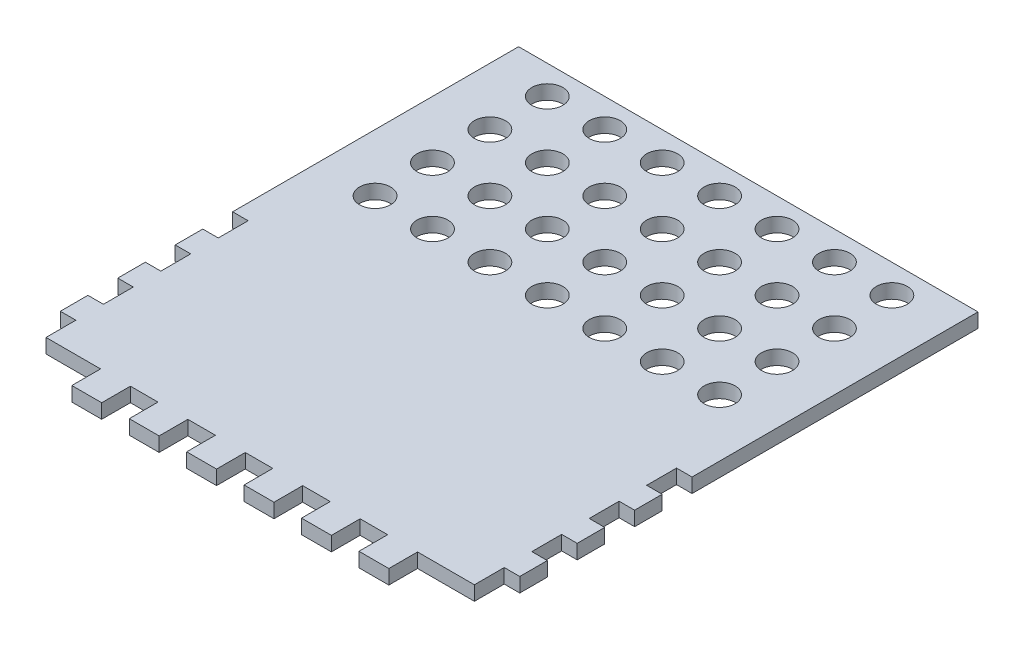
SolidWorks part; units mm, degrees
ref_plane "Front Plane" through (0, 0, 0) normal (0, 0, 1) x (1, 0, 0)
ref_plane "Top Plane" through (0, 0, 0) normal (0, 1, 0) x (1, 0, 0)
ref_plane "Right Plane" through (0, 0, 0) normal (1, 0, 0) x (0, 0, -1)
sketch "Sketch1" plane through (0, 0, 0) normal (0, 1, 0) x (1, 0, 0)
  line L1 (-50.8, -53.975) -> (50.8, -53.975)
  line L2 (-50.8, -53.975) -> (-50.8, 53.975)
  line L3 (-50.8, 53.975) -> (50.8, 53.975)
  line L4 (50.8, -53.975) -> (50.8, 53.975)
  line L5 (-50.8, -53.975) -> (50.8, 53.975) construction
  line L6 (-50.8, 53.975) -> (50.8, -53.975) construction
  line L11 (-41.275, -53.975) -> (41.275, 53.975) construction
  line L12 (-41.275, 53.975) -> (41.275, -53.975) construction
  point P0 (0, 0)
  point P5 (0, 0)
  dimension "D1" = 101.6
  dimension "D2" = 107.95
extrude "Boss-Extrude1" add sketch "Sketch1" along normal blind 3.175
sketch "Sketch2" plane through (0, 3.175, 0) normal (0, 1, 0) x (1, 0, 0)
  line L37 (22.098, -47.625) -> (28.194, -47.625)
  line L49 (28.194, -47.625) -> (28.194, -54.229)
  line L69 (0, 0) -> (0, -10.121) construction
  line L74 (-50.8, 53.975) -> (-50.8, -53.975) construction
  line L75 (-47.371, 28.448) -> (-50.8, 28.448)
  line L76 (-47.371, 28.448) -> (-47.371, 35.052)
  line L78 (-50.8, 28.448) -> (-50.8, 35.052)
  line L79 (-47.371, 22.479) -> (-50.8, 22.479)
  line L80 (-47.371, 22.479) -> (-47.371, 15.875)
  line L81 (-47.371, 15.875) -> (-50.8, 15.875)
  line L82 (-50.8, 22.479) -> (-50.8, 15.875)
  line L83 (-47.371, 9.779) -> (-50.8, 9.779)
  line L84 (-47.371, 9.779) -> (-47.371, 3.175)
  line L85 (-47.371, 3.175) -> (-50.8, 3.175)
  line L86 (-50.8, 9.779) -> (-50.8, 3.175)
  line L87 (-47.371, -2.921) -> (-50.8, -2.921)
  line L88 (-47.371, -2.921) -> (-47.371, -9.525)
  line L89 (-47.371, -9.525) -> (-50.8, -9.525)
  line L90 (-50.8, -2.921) -> (-50.8, -9.525)
  line L91 (-47.371, -15.621) -> (-50.8, -15.621)
  line L92 (-47.371, -15.621) -> (-47.371, -22.225)
  line L93 (-47.371, -22.225) -> (-50.8, -22.225)
  line L94 (-50.8, -15.621) -> (-50.8, -22.225)
  line L95 (-47.371, -28.321) -> (-50.8, -28.321)
  line L96 (-47.371, -28.321) -> (-47.371, -34.925)
  line L97 (-47.371, -34.925) -> (-50.8, -34.925)
  line L98 (-50.8, -28.321) -> (-50.8, -34.925)
  line L99 (-47.371, -41.021) -> (-50.8, -41.021)
  line L100 (-47.371, -41.021) -> (-47.371, -47.625)
  line L102 (-50.8, -41.021) -> (-50.8, -47.625)
  line L118 (50.8, -41.021) -> (50.8, -47.625)
  line L120 (47.371, -41.021) -> (47.371, -47.625)
  line L121 (47.371, -41.021) -> (50.8, -41.021)
  line L122 (50.8, -28.321) -> (50.8, -34.925)
  line L123 (47.371, -34.925) -> (50.8, -34.925)
  line L124 (47.371, -28.321) -> (47.371, -34.925)
  line L125 (47.371, -28.321) -> (50.8, -28.321)
  line L126 (50.8, -15.621) -> (50.8, -22.225)
  line L127 (47.371, -22.225) -> (50.8, -22.225)
  line L128 (47.371, -15.621) -> (47.371, -22.225)
  line L129 (47.371, -15.621) -> (50.8, -15.621)
  line L130 (50.8, -2.921) -> (50.8, -9.525)
  line L131 (47.371, -9.525) -> (50.8, -9.525)
  line L132 (47.371, -2.921) -> (47.371, -9.525)
  line L133 (47.371, -2.921) -> (50.8, -2.921)
  line L134 (50.8, 9.779) -> (50.8, 3.175)
  line L135 (47.371, 3.175) -> (50.8, 3.175)
  line L136 (47.371, 9.779) -> (47.371, 3.175)
  line L137 (47.371, 9.779) -> (50.8, 9.779)
  line L138 (50.8, 22.479) -> (50.8, 15.875)
  line L139 (47.371, 15.875) -> (50.8, 15.875)
  line L140 (47.371, 22.479) -> (47.371, 15.875)
  line L141 (47.371, 22.479) -> (50.8, 22.479)
  line L150 (-47.371, -53.721) -> (-50.8, -53.721) [skipped]
  line L151 (-47.371, -53.721) -> (-47.371, -60.325) [skipped]
  line L152 (-47.371, -60.325) -> (-50.8, -60.325) [skipped]
  line L153 (-50.8, -53.721) -> (-50.8, -60.325) [skipped]
  line L154 (-50.8, 35.052) -> (-47.371, 35.052)
  line L155 (50.8, 35.052) -> (47.371, 35.052)
  line L156 (50.8, 28.448) -> (50.8, 35.052)
  line L157 (47.371, 28.448) -> (47.371, 35.052)
  line L158 (47.371, 28.448) -> (50.8, 28.448)
  line L159 (-47.371, -47.625) -> (-35.306, -47.625)
  line L160 (-35.306, -47.625) -> (-35.306, -54.229)
  line L161 (-35.306, -54.229) -> (-28.702, -54.229)
  line L162 (-28.702, -54.229) -> (-28.702, -47.625)
  line L163 (-28.702, -47.625) -> (-22.606, -47.625)
  line L164 (-22.606, -47.625) -> (-22.606, -54.229)
  line L165 (-22.606, -54.229) -> (-16.002, -54.229)
  line L166 (-16.002, -54.229) -> (-16.002, -47.625)
  line L167 (-16.002, -47.625) -> (-9.906, -47.625)
  line L168 (-9.906, -47.625) -> (-9.906, -54.229)
  line L169 (-9.906, -54.229) -> (-3.302, -54.229)
  line L170 (-3.302, -54.229) -> (-3.302, -47.625)
  line L171 (-3.302, -47.625) -> (2.794, -47.625)
  line L172 (2.794, -47.625) -> (2.794, -54.229)
  line L173 (2.794, -54.229) -> (9.398, -54.229)
  line L174 (9.398, -54.229) -> (9.398, -47.625)
  line L175 (9.398, -47.625) -> (15.494, -47.625)
  line L176 (15.494, -47.625) -> (15.494, -54.229)
  line L177 (15.494, -54.229) -> (22.098, -54.229)
  line L178 (22.098, -54.229) -> (22.098, -47.625)
  line L180 (-50.8, -47.625) -> (-50.8, -92.545)
  line L181 (-47.371, -47.625) -> (-50.8, -47.625) [skipped]
  line L182 (-50.8, -92.545) -> (50.8, -92.545)
  line L183 (50.8, -92.545) -> (50.8, -47.625)
  line L184 (28.194, -54.229) -> (34.798, -54.229)
  line L185 (34.798, -54.229) -> (34.798, -47.625)
  line L186 (34.798, -47.625) -> (47.371, -47.625)
  line L187 (50.8, 53.975) -> (-50.8, 53.975) construction
  line L188 (50.8, 47.752) -> (47.371, 47.752)
  line L189 (50.8, 41.148) -> (50.8, 47.752)
  line L190 (47.371, 41.148) -> (47.371, 47.752)
  line L191 (47.371, 41.148) -> (50.8, 41.148)
  line L192 (-47.371, 41.148) -> (-50.8, 41.148)
  line L193 (-47.371, 41.148) -> (-47.371, 47.752)
  line L194 (-50.8, 41.148) -> (-50.8, 47.752)
  line L195 (-50.8, 47.752) -> (-47.371, 47.752)
  point P0 (-28.702, -50.927)
  dimension "D2" = 15.494
  dimension "D3" = 6.604
  dimension "D5" = 6.096
  dimension "D6" = 101.6
  dimension "D7" = 6.604
  dimension "D8" = 3.429
  dimension "D9" = 2
  dimension "D10" = 6.604
  dimension "D12" = 2
  dimension "D4" = 6.096
  dimension "D14" = 5.969
  dimension "D11" = 7
extrude "Cut-Extrude1" cut sketch "Sketch2" against normal through all both and the other way through all
sketch "Sketch3" plane through (0, 3.175, 0) normal (0, 1, 0) x (1, 0, 0)
  line L0 (-47.371, -47.625) -> (-35.306, -47.625) construction
  line L1 (-50.8, 53.975) -> (50.8, 53.975)
  line L2 (-50.8, 53.975) -> (-50.8, 3.175)
  line L3 (-50.8, 3.175) -> (50.8, 3.175)
  line L4 (50.8, 53.975) -> (50.8, 3.175)
  line L5 (50.8, 35.052) -> (50.8, 41.148) construction
  dimension "D1" = 50.8
extrude "Cut-Extrude2" cut sketch "Sketch3" against normal through all
sketch "Sketch4" plane through (0, 3.175, 0) normal (0, 1, 0) x (1, 0, 0)
  line L0 (50.8, -2.921) -> (50.8, 3.175) construction
  line L1 (-50.8, 3.175) -> (50.8, 3.175)
  line L2 (-50.8, 3.175) -> (-50.8, 60.325)
  line L3 (-50.8, 60.325) -> (50.8, 60.325)
  line L4 (50.8, 3.175) -> (50.8, 60.325)
  circle A0 centre (-38.1, 15.875) radius 3.429
  circle A1 centre (-25.4, 15.875) radius 3.429
  circle A2 centre (-12.7, 15.875) radius 3.429
  circle A3 centre (0, 15.875) radius 3.429
  circle A4 centre (12.7, 15.875) radius 3.429
  circle A5 centre (25.4, 15.875) radius 3.429
  circle A6 centre (38.1, 15.875) radius 3.429
  circle A8 centre (-25.4, 28.575) radius 3.429
  circle A9 centre (-12.7, 28.575) radius 3.429
  circle A10 centre (0, 28.575) radius 3.429
  circle A11 centre (12.7, 28.575) radius 3.429
  circle A12 centre (25.4, 28.575) radius 3.429
  circle A13 centre (38.1, 28.575) radius 3.429
  circle A15 centre (-25.4, 41.275) radius 3.429
  circle A16 centre (-12.7, 41.275) radius 3.429
  circle A17 centre (0, 41.275) radius 3.429
  circle A18 centre (12.7, 41.275) radius 3.429
  circle A19 centre (25.4, 41.275) radius 3.429
  circle A20 centre (38.1, 41.275) radius 3.429
  circle A22 centre (-25.4, 53.975) radius 3.429
  circle A23 centre (-12.7, 53.975) radius 3.429
  circle A24 centre (0, 53.975) radius 3.429
  circle A25 centre (12.7, 53.975) radius 3.429
  circle A26 centre (25.4, 53.975) radius 3.429
  circle A27 centre (38.1, 53.975) radius 3.429
  circle A29 centre (-38.1, 28.575) radius 3.429
  circle A30 centre (-38.1, 41.275) radius 3.429
  circle A31 centre (-38.1, 53.975) radius 3.429
  dimension "D2" = 6.858
  dimension "D1" = 57.15
  dimension "D3" = 12.7
  dimension "D4" = 12.7
  dimension "D5" = 7
  dimension "D6" = 4
extrude "Boss-Extrude2" add sketch "Sketch4" against normal blind 3.175
